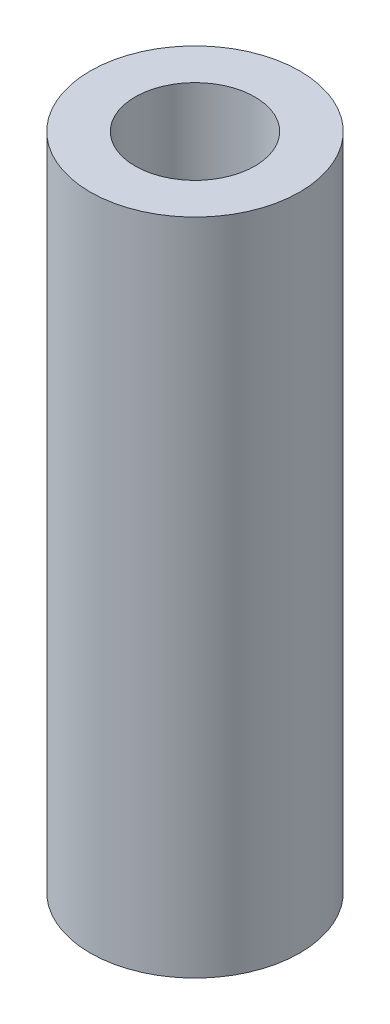
SolidWorks part; units mm, degrees
material "尼龙 101"
ref_plane "前视基准面" through (0, 0, 0) normal (0, 0, 1) x (1, 0, 0)
ref_plane "上视基准面" through (0, 0, 0) normal (0, 1, 0) x (1, 0, 0)
ref_plane "右视基准面" through (0, 0, 0) normal (1, 0, 0) x (0, 0, -1)
sketch "草图1" plane through (0, 0, 0) normal (0, 1, 0) x (1, 0, 0)
  circle A0 centre (0, 0) radius 3.5
  circle A1 centre (0, 0) radius 2
  dimension "D1" = 4
  dimension "D2" = 7
extrude "凸台-拉伸1" add sketch "草图1" along normal blind 22
